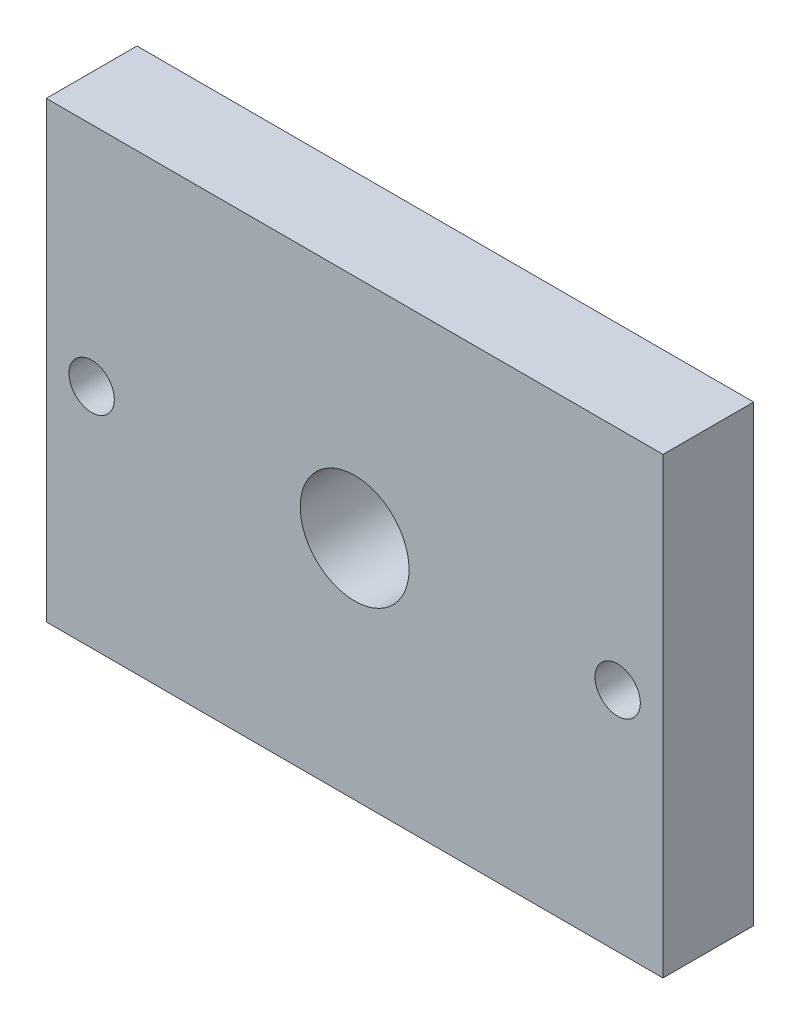
SolidWorks part; units mm, degrees
ref_plane "Front Plane" through (0, 0, 0) normal (0, 0, 1) x (1, 0, 0)
ref_plane "Top Plane" through (0, 0, 0) normal (0, 1, 0) x (1, 0, 0)
ref_plane "Right Plane" through (0, 0, 0) normal (1, 0, 0) x (0, 0, -1)
sketch "Sketch1" plane through (0, 0, 0) normal (0, 0, 1) x (1, 0, 0)
  line L1 (-34, 25) -> (34, 25)
  line L2 (-34, 25) -> (-34, -25)
  line L3 (-34, -25) -> (34, -25)
  line L4 (34, 25) -> (34, -25)
  line L5 (-34, 25) -> (34, -25) construction
  line L6 (-34, -25) -> (34, 25) construction
  circle A0 centre (0, 0) radius 6
  circle A1 centre (29, 0) radius 2.5
  circle A2 centre (-29, 0) radius 2.5
  point P0 (0, 0)
  dimension "D3" = 12
  dimension "D4" = 5
  dimension "D5" = 5
  dimension "D1" = 50
  dimension "D2" = 68
  dimension "D6" = 5
  dimension "D7" = 5
extrude "Boss-Extrude1" add sketch "Sketch1" along normal blind 10
